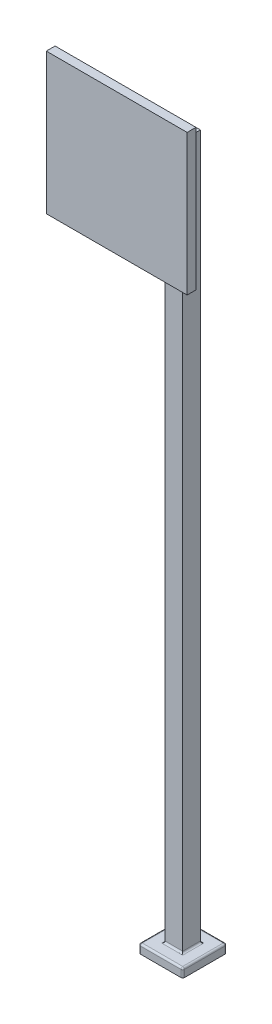
SolidWorks part; units mm, degrees
ref_plane "Front Plane" through (0, 0, 0) normal (0, 0, 1) x (1, 0, 0)
ref_plane "Top Plane" through (0, 0, 0) normal (0, 1, 0) x (1, 0, 0)
ref_plane "Right Plane" through (0, 0, 0) normal (1, 0, 0) x (0, 0, -1)
sketch "Sketch1" plane through (0, 0, 0) normal (0, 0, 1) x (1, 0, 0)
  line L1 (-50, 4000) -> (50, 4000)
  line L2 (-50, 4000) -> (-50, 0)
  line L3 (-50, 0) -> (50, 0)
  line L4 (50, 4000) -> (50, 0)
  point P4 (0, 0)
  dimension "D1" = 4000
  dimension "D2" = 100
extrude "Boss-Extrude1" add sketch "Sketch1" along normal mid plane 100
sketch "Sketch2" plane through (0, 0, 0) normal (0, 1, 0) x (1, 0, 0)
  line L1 (-125, 125) -> (125, 125)
  line L2 (-125, 125) -> (-125, -125)
  line L3 (-125, -125) -> (125, -125)
  line L4 (125, 125) -> (125, -125)
  line L5 (-125, 125) -> (125, -125) construction
  line L6 (-125, -125) -> (125, 125) construction
  point P0 (0, 0)
  dimension "D1" = 250
extrude "Boss-Extrude2" add sketch "Sketch2" against normal blind 50
sketch "Sketch3" plane through (0, 0, 0) normal (1, 0, 0) x (0, 0, -1)
  line L1 (50, 4000) -> (-350, 4000)
  line L2 (50, 4000) -> (50, 3950)
  line L3 (50, 3950) -> (-350, 3950)
  line L4 (-350, 4000) -> (-350, 3950)
  dimension "D1" = 50
  dimension "D2" = 400
extrude "Boss-Extrude3" add sketch "Sketch3" against normal mid plane 50
sketch "Sketch4" plane through (0, 0, 350) normal (0, 0, 1) x (1, 0, 0)
  line L0 (25, 4000) -> (25, 3950) construction
  line L1 (-400, 4375) -> (400, 4375)
  line L2 (-400, 4375) -> (-400, 3575)
  line L3 (-400, 3575) -> (400, 3575)
  line L4 (400, 4375) -> (400, 3575)
  line L5 (-400, 4375) -> (400, 3575) construction
  line L6 (-400, 3575) -> (400, 4375) construction
  line L7 (-25, 4000) -> (25, 4000) construction
  point P0 (0, 3975)
  point P5 (0, 0)
  point P8 (25, 3975)
  point P11 (0, 4000)
  dimension "D1" = 800
extrude "Boss-Extrude4" add sketch "Sketch4" along normal mid plane 50
fillet "Fillet1" radius 10 12 edges at (0, 0, -125) (-125, 0, 0) (0, 0, 125) (125, -25, -125) (-125, -25, -125) (-125, -25, 125) (0, 0, -50) (0, 0, 50) (50, 0, 0) (-50, 0, 0) (125, 0, 0) (125, -25, 125)
fillet "Fillet3" radius 10 4 edges at (-25, 3975, 50) (-25, 3975, 325) (25, 3975, 325) (25, 3975, 50)
fillet "Fillet4" radius 10 2 edges at (0, 3950, 325) (0, 4000, 325)
